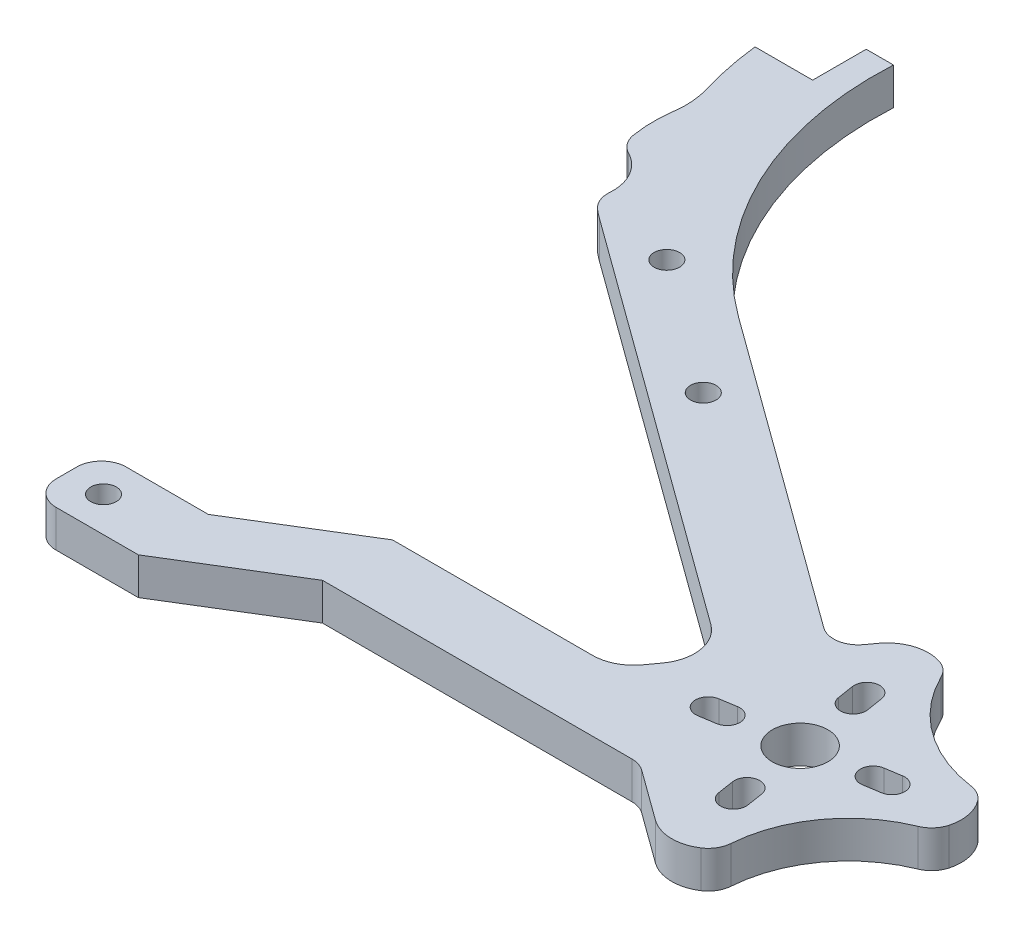
SolidWorks part; units mm, degrees
material "PPS"
ref_plane "前视基准面" through (0, 0, 0) normal (0, 0, 1) x (1, 0, 0)
ref_plane "上视基准面" through (0, 0, 0) normal (0, 1, 0) x (1, 0, 0)
ref_plane "右视基准面" through (0, 0, 0) normal (1, 0, 0) x (0, 0, -1)
sketch "草图3" plane through (0, 0, 0) normal (0, 1, 0) x (1, 0, 0)
  line L0 (0, 0) -> (35.4735, 0) construction
  line L1 (0, 0) -> (62.3757, -45.3186) construction
  line L2 (41.1319, -24.0128) -> (94.6944, -62.9282)
  line L3 (94.6944, -62.9282) -> (100.1314, -55.4448)
  line L4 (100.1314, -55.4448) -> (122.7839, -71.9028)
  line L5 (122.7839, -71.9028) -> (106.3259, -94.5552)
  line L6 (83.6734, -78.0972) -> (106.3259, -94.5552) construction
  line L9 (77.9994, -109.7251) -> (128.6275, -40.0415) construction
  line L11 (103.2286, -75) -> (90.242, -77.0569) construction
  line L13 (110.8832, -73.7876) -> (112.8586, -73.4748) construction
  line L14 (110.6408, -72.2567) -> (112.6161, -71.9438)
  line L15 (111.1257, -75.3185) -> (113.1011, -75.0057)
  line L16 (102.0163, -67.3454) -> (101.7034, -65.37) construction
  line L17 (103.5472, -67.1029) -> (103.2343, -65.1276)
  line L18 (100.4854, -67.5879) -> (100.1725, -65.6125)
  line L19 (95.5741, -76.2124) -> (93.5987, -76.5252) construction
  line L20 (95.8165, -77.7433) -> (93.8412, -78.0562)
  line L21 (95.3316, -74.6815) -> (93.3562, -74.9943)
  line L22 (104.441, -82.6546) -> (104.7539, -84.63) construction
  line L23 (102.9101, -82.8971) -> (103.223, -84.8724)
  line L24 (105.9719, -82.4121) -> (106.2848, -84.3875)
  line L36 (68.8077, -72) -> (90.242, -72) construction
  line L49 (89.1104, -70.6138) -> (83.6734, -78.0972)
  line L50 (35.5479, -31.6984) -> (89.1104, -70.6138)
  line L51 (83.6734, -78.0972) -> (30, -78.0972) construction
  line L52 (30, -78.0972) -> (30, -86.5972) construction
  line L53 (30, -86.5972) -> (95.3727, -86.5972) construction
  line L54 (95.3727, -86.5972) -> (106.3259, -94.5552)
  line L55 (83.6734, -78.0972) -> (56.8367, -78.0972)
  line L56 (95.3727, -86.5972) -> (56.8367, -86.5972)
  line L57 (56.8367, -78.0972) -> (42.9738, -86.5972)
  line L58 (42.9738, -86.5972) -> (30, -86.5972)
  line L59 (56.8367, -86.5972) -> (42.9738, -95.0972)
  line L60 (30, -86.5972) -> (30, -95.0972)
  line L61 (30, -95.0972) -> (42.9738, -95.0972)
  circle A5 centre (103.2286, -75) radius 3.375
  arc A6 (110.6408, -72.2567) -> (111.1257, -75.3185) centre (110.8832, -73.7876) ccw
  arc A7 (113.1011, -75.0057) -> (112.6161, -71.9438) centre (112.8586, -73.4748) ccw
  arc A8 (103.5472, -67.1029) -> (100.4854, -67.5879) centre (102.0163, -67.3454) cw
  arc A9 (100.1725, -65.6125) -> (103.2343, -65.1276) centre (101.7034, -65.37) cw
  arc A10 (95.8165, -77.7433) -> (95.3316, -74.6815) centre (95.5741, -76.2124) ccw
  arc A11 (93.3562, -74.9943) -> (93.8412, -78.0562) centre (93.5987, -76.5252) ccw
  arc A12 (102.9101, -82.8971) -> (105.9719, -82.4121) centre (104.441, -82.6546) cw
  arc A13 (106.2848, -84.3875) -> (103.223, -84.8724) centre (104.7539, -84.63) cw
  arc A16 (41.1319, -24.0128) -> (35.5479, -31.6984) centre (38.3399, -27.8556) ccw
  circle A17 centre (103.2286, -75) radius 66.25 construction
  circle A18 centre (44.0442, -32) radius 1.55
  circle A19 centre (60.2246, -43.7557) radius 1.55
  circle A20 centre (34.5, -90.8472) radius 1.55
  point P11 (114.5549, -83.229)
  point P20 (111.8709, -73.6312)
  point P27 (101.8598, -66.3577)
  point P35 (94.5864, -76.3688)
  point P42 (104.5974, -83.6423)
  point P54 (94.9997, -86.3262)
  point P69 (30, -90.8472)
  dimension "D2" = 45
  dimension "D3" = 6.75
  dimension "D4" = 1.55
  dimension "D7" = 14
  dimension "D11" = 132.5
  dimension "D12" = 3.1
  dimension "D16" = 3.1
  dimension "D1" = 36
  dimension "D5" = 2
  dimension "D6" = 7.75
  dimension "D8" = 14
  dimension "D9" = 4.75
  dimension "D10" = 75
  dimension "D13" = 32
  dimension "D14" = 20
  dimension "D15" = 8.5
  dimension "D17" = 34.5
  dimension "D18" = 4.5
  dimension "D19" = 90.8472
  dimension "D22" = 72
extrude "凸台-拉伸1" add sketch "草图3" along normal blind 4.5
fillet "圆角-美观1" radius 5 5 edges at (100.1314, 2.25, 55.4448) (122.7839, 2.25, 71.9028) (89.1104, 2.25, 70.6138) (106.3259, 2.25, 94.5552) (83.6734, 2.25, 78.0972)
sketch "草图4" plane through (0, 4.5, 0) normal (0, 1, 0) x (1, 0, 0)
  line L0 (104.1765, -58.3837) -> (118.7388, -68.9638)
  line L1 (119.8449, -75.9478) -> (109.2648, -90.5101)
  line L3 (103.2286, -75) -> (124.6569, -90.5685) construction
  line L4 (103.2286, -75) -> (89.033, -94.5387) construction
  line L5 (87.7185, -81.0362) -> (102.2808, -91.6163)
  arc A2 (102.2808, -91.6163) -> (87.7185, -81.0362) centre (86.1651, -98.4859) ccw
  arc A8 (118.7388, -68.9638) -> (104.1765, -58.3837) centre (120.2922, -51.5141) cw
  arc A9 (119.8449, -75.9478) -> (109.2648, -90.5101) centre (124.6569, -90.5685) ccw
  line M2 (118.7388, -68.9638) -> (104.1765, -58.3837)
  line M12 (109.2648, -90.5101) -> (119.8449, -75.9478)
extrude "圆弧-美观2" cut sketch "草图4" against normal up to next contours A8 M2 | A9 M12
fillet "圆角-美观3" radius 3 8 edges at (104.1765, 2.25, 58.3837) (118.7388, 2.25, 68.9638) (119.8449, 2.25, 75.9478) (94.6944, 2.25, 62.9282) (109.2648, 2.25, 90.5101) (30, 2.25, 95.0972) (95.3727, 2.25, 86.5972) (30, 2.25, 86.5972)
sketch "草图5" plane through (0, 0, 0) normal (0, 1, 0) x (1, 0, 0)
  line L0 (0, 0) -> (158.8801, 0) construction
  line L1 (0, 0) -> (0, -78.2587) construction
  line L2 (29.255, -13.8932) -> (40.1931, -23.471) construction
  line L3 (27.0025, -4.25) -> (34, -4.25)
  line L4 (34, -4.25) -> (34, 2.25)
  line L5 (34, -3.25) -> (26.9026, -3.25) construction
  line L6 (34, 3.25) -> (34, -3.25) construction
  line L7 (37.3772, 3.25) -> (34, 3.25) construction
  line L8 (41.1319, -24.0128) -> (54.395, -33.649)
  line L9 (34, 2.25) -> (37.3109, 2.25)
  line L10 (35.5479, -31.6984) -> (85.0653, -67.6749) construction
  line L11 (41.1319, -24.0128) -> (35.5479, -31.6984)
  arc A0 (26.9026, -3.25) -> (28.5167, -11.6611) centre (68.8233, 0.4342) ccw construction
  arc A5 (41.1319, -24.0128) -> (40.1931, -23.471) centre (38.2952, -27.8445) ccw
  arc A7 (40.1931, -23.471) -> (35.5479, -31.6984) centre (38.3022, -27.8285) ccw construction
  arc A8 (35.5479, -31.6984) -> (28.8424, -15.919) centre (45.3379, -18.2237) cw
  arc A9 (28.8424, -15.919) -> (28.5167, -11.6611) centre (18.9386, -14.5353) ccw
  arc A11 (37.3772, 3.25) -> (54.395, -33.649) centre (78.8424, 0) ccw
  arc A12 (27.0025, -4.25) -> (28.5167, -11.6611) centre (68.8233, 0.4342) ccw
  arc A13 (29.8202, 19.4008) -> (29.8202, -19.4008) centre (91.9966, 0) ccw construction
  arc A14 (54.395, 33.649) -> (54.395, -33.649) centre (78.8424, 0) ccw construction
  arc A15 (29.9602, 19.3706) -> (29.9602, -19.3706) centre (67.3193, 0) ccw construction
  dimension "D1" = 3.25
  dimension "D2" = 3.25
  dimension "D3" = 34
  dimension "D4" = 1
  dimension "D5" = 1
extrude "机臂配合防旋转" add sketch "草图5" along normal up to surface (4.5 mm away) up to face at (60.2246, 4.5, 45.3057)
sketch "草图7" plane through (0, 0, 0) normal (0, 1, 0) x (1, 0, 0)
  circle A6 centre (28, -28) radius 3.15 construction
  circle A7 centre (28, -28) radius 5.5
  circle A8 centre (44.0442, -32) radius 1.55 construction
  dimension "D1" = 11
  dimension "D2" = 16.0442
  dimension "D3" = 4
extrude "减震球让位" cut sketch "草图7" along normal through all
fillet "圆角1" radius 3 2 edges at (33.2399, 2.25, 29.6714) (29.2815, 2.25, 22.6514)
